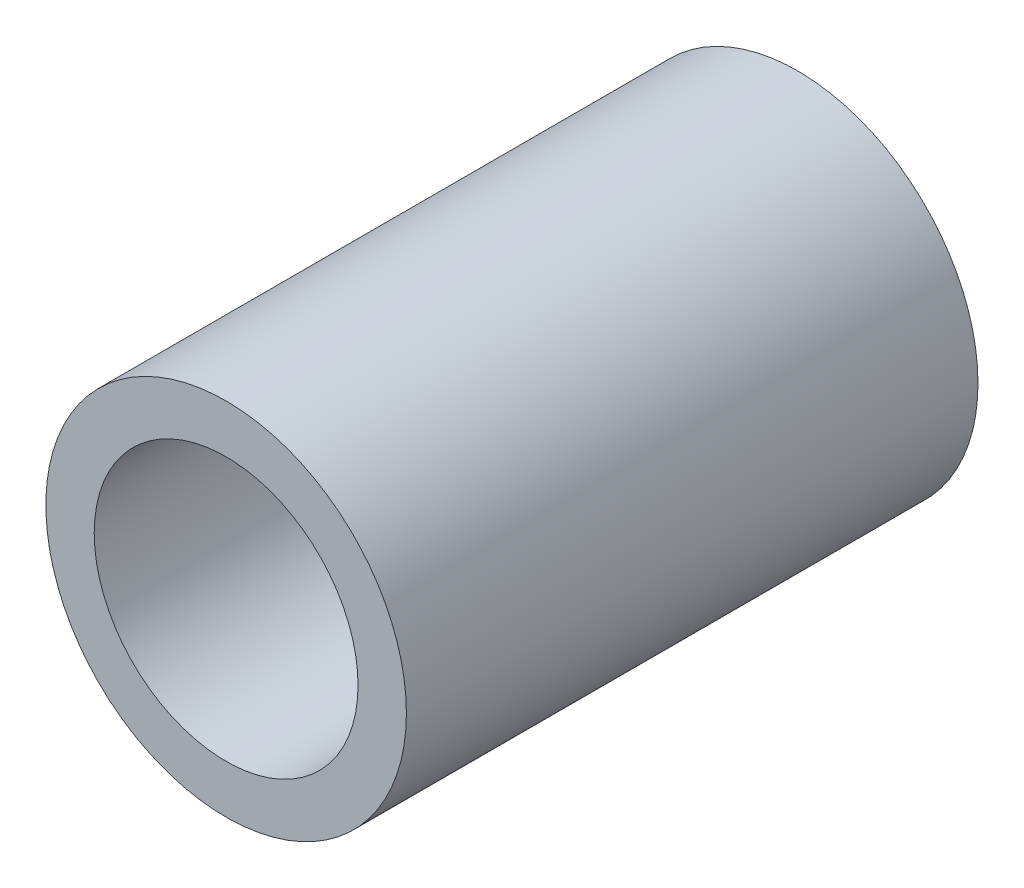
SolidWorks part; units mm, degrees
ref_plane "Front Plane" through (0, 0, 0) normal (0, 0, 1) x (1, 0, 0)
ref_plane "Top Plane" through (0, 0, 0) normal (0, 1, 0) x (1, 0, 0)
ref_plane "Right Plane" through (0, 0, 0) normal (1, 0, 0) x (0, 0, -1)
sketch "Sketch1" plane through (0, 0, 0) normal (0, 0, 1) x (1, 0, 0)
  circle A0 centre (0, 0) radius 41
  dimension "D1" = 82
extrude "Boss-Extrude1" add sketch "Sketch1" along normal blind 130
sketch "Sketch2" plane through (0, 0, 130) normal (0, 0, 1) x (1, 0, 0)
  circle A0 centre (0, 0) radius 30
  circle A1 centre (0, 0) radius 41 construction
  dimension "D1" = 11
extrude "Cut-Extrude3" cut sketch "Sketch2" against normal blind 140
